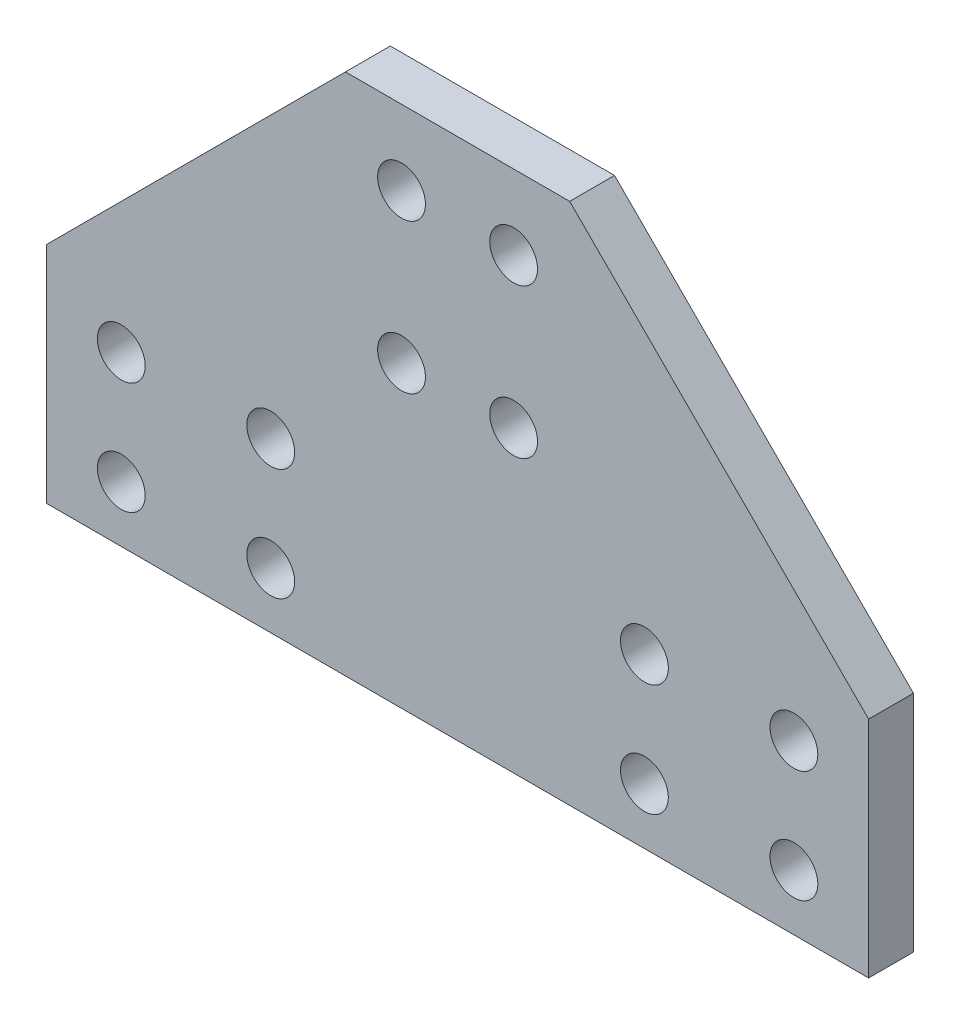
SolidWorks part; units mm, degrees
ref_plane "前视基准面" through (0, 0, 0) normal (0, 0, 1) x (1, 0, 0)
ref_plane "上视基准面" through (0, 0, 0) normal (0, 1, 0) x (1, 0, 0)
ref_plane "右视基准面" through (0, 0, 0) normal (1, 0, 0) x (0, 0, -1)
other "Configuration Table"
sketch "草图1" plane through (0, 0, 0) normal (0, 0, 1) x (1, 0, 0)
  line L0 (0, 0) -> (15, 0)
  line L1 (15, 0) -> (35, -20)
  line L2 (35, -20) -> (35, -35)
  line L3 (35, -35) -> (-20, -35)
  line L4 (-20, -35) -> (-20, -20)
  line L5 (-20, -20) -> (0, 0)
  line L6 (7.5, 0) -> (7.5, -35) construction
  dimension "D1" = 15
  dimension "D2" = 15
  dimension "D3" = 15
  dimension "D4" = 55
  dimension "D5" = 20
extrude "凸台-拉伸1" add sketch "草图1" along normal blind 3
sketch "草图2" plane through (0, 0, 3) normal (0, 0, 1) x (1, 0, 0)
  line L0 (7.5, 0) -> (7.5, -35) construction
  line L1 (15, 0) -> (0, 0) construction
  line L2 (-20, -35) -> (35, -35) construction
  line L3 (-20, -27.5) -> (35, -27.5) construction
  line L4 (-20, -20) -> (-20, -35) construction
  line L5 (35, -35) -> (35, -20) construction
  line L6 (-10, -27.5) -> (-10, -35) construction
  line L7 (7.5, -10) -> (25, -10) construction
  line L8 (35, -20) -> (15, 0) construction
  circle A0 centre (-15, -31.25) radius 1.6
  circle A1 centre (-15, -23.75) radius 1.6
  circle A2 centre (-5, -31.25) radius 1.6
  circle A3 centre (-5, -23.75) radius 1.6
  circle A4 centre (20, -31.25) radius 1.6
  circle A5 centre (30, -31.25) radius 1.6
  circle A6 centre (20, -23.75) radius 1.6
  circle A7 centre (30, -23.75) radius 1.6
  circle A8 centre (3.75, -5) radius 1.6
  circle A9 centre (11.25, -5) radius 1.6
  circle A10 centre (11.25, -15) radius 1.6
  circle A11 centre (3.75, -15) radius 1.6
  dimension "D1" = 3.2
  dimension "D5" = 10
  dimension "D6" = 3.2
  dimension "D2" = 5
  dimension "D3" = 10
  dimension "D4" = 3.75
  dimension "D7" = 3.75
  dimension "D8" = 5
extrude "切除-拉伸1" cut sketch "草图2" against normal through all
